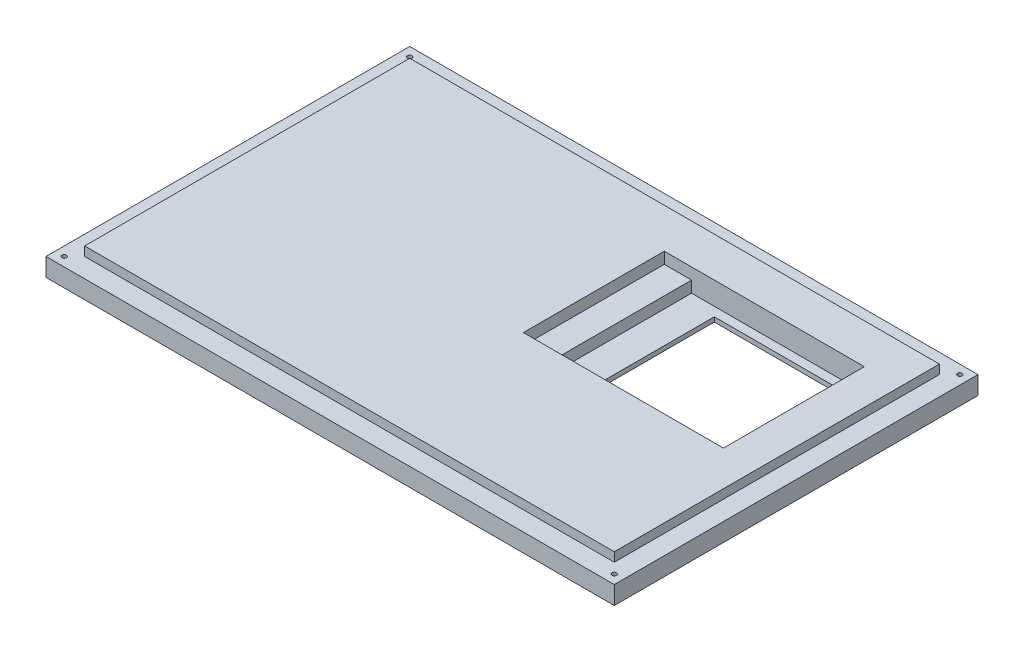
SolidWorks part; units mm, degrees
ref_plane "Front Plane" through (0, 0, 0) normal (0, 0, 1) x (1, 0, 0)
ref_plane "Top Plane" through (0, 0, 0) normal (0, 1, 0) x (1, 0, 0)
ref_plane "Right Plane" through (0, 0, 0) normal (1, 0, 0) x (0, 0, -1)
sketch "base sketch" plane through (0, 0, 0) normal (0, 1, 0) x (1, 0, 0)
  line L1 (0, 0) -> (125, 0)
  line L2 (0, 0) -> (0, 80)
  line L3 (0, 80) -> (125, 80)
  line L4 (125, 0) -> (125, 80)
  dimension "D1" = 80
  dimension "D2" = 125
extrude "base extrude" add sketch "base sketch" along normal blind 4
ref_plane "inset plane" through (0, 4, 0) normal (0, 1, 0) x (1, 0, 0)
sketch "inset sketch" plane through (0, 4, 0) normal (0, 1, 0) x (1, 0, 0)
  line L0 (0, 80) -> (0, 0) construction
  line L1 (4.25, 75.75) -> (120.75, 75.75)
  line L2 (4.25, 75.75) -> (4.25, 4.25)
  line L3 (4.25, 4.25) -> (120.75, 4.25)
  line L4 (120.75, 75.75) -> (120.75, 4.25)
  line L5 (125, 80) -> (0, 80) construction
  line L6 (125, 0) -> (125, 80) construction
  line L7 (0, 0) -> (125, 0) construction
  dimension "D1" = 4.25
  dimension "D2" = 4.25
  dimension "D3" = 4.25
  dimension "D4" = 4.25
extrude "inset extrude" add sketch "inset sketch" along normal blind 2
ref_plane "inner hole plane" through (0, 6, 0) normal (0, 1, 0) x (1, 0, 0)
sketch "inner hole sketch" plane through (0, 6, 0) normal (0, 1, 0) x (1, 0, 0)
  line L0 (125, 80) -> (0, 80) construction
  line L1 (82, 65) -> (110, 65)
  line L2 (82, 65) -> (82, 38)
  line L3 (82, 38) -> (110, 38)
  line L4 (110, 65) -> (110, 38)
  line L5 (125, 0) -> (125, 80) construction
  dimension "D1" = 28
  dimension "D2" = 27
  dimension "D3" = 15
  dimension "D4" = 15
extrude "inner hole cut" cut sketch "inner hole sketch" against normal blind 12
sketch "outer hole sketch" plane through (0, 6, 0) normal (0, 1, 0) x (1, 0, 0)
  line L0 (82, 65) -> (82, 38) construction
  line L1 (69, 67) -> (113, 67)
  line L2 (69, 67) -> (69, 36)
  line L3 (69, 36) -> (113, 36)
  line L4 (113, 67) -> (113, 36)
  line L5 (110, 65) -> (82, 65) construction
  dimension "D1" = 44
  dimension "D2" = 13
  dimension "D3" = 31
  dimension "D4" = 2
extrude "outter hole cut" cut sketch "outer hole sketch" against normal blind 2.5
sketch "middle hole sketch" plane through (0, 6, 0) normal (0, 1, 0) x (1, 0, 0)
  line L0 (113, 36) -> (113, 67) construction
  line L1 (113, 67) -> (75, 67)
  line L2 (113, 67) -> (113, 36)
  line L3 (113, 36) -> (75, 36)
  line L4 (75, 67) -> (75, 36)
  line L5 (113, 36) -> (113, 67) construction
  line L6 (69, 36) -> (113, 36) construction
  line L7 (69, 67) -> (69, 36) construction
  dimension "D1" = 6
  dimension "D2" = 31
extrude "middle hole cut" cut sketch "middle hole sketch" against normal blind 5
hole_wizard "Ø1.0mm Dowel Hole1" positions "3DSketch2" profile "Sketch7" hole size "Ø1.0" standard "ANSI Metric" end condition up to next
sketch3d "3DSketch2"
  line L0 (125, 0, 0) -> (125, 0, -80) construction
  line L1 (125, 0, -80) -> (0, 0, -80) construction
  line L2 (0, 0, 0) -> (125, 0, 0) construction
  line L3 (0, 0, -80) -> (0, 0, 0) construction
  point P0 (123, 0, -78)
  point P2 (123, 0, -2)
  point P4 (2, 0, -2)
  point P6 (2, 0, -78)
  point P17 (0, 0, 0)
  dimension "D1" = 2
  dimension "D2" = 2
  dimension "D3" = 2
  dimension "D4" = 2
  dimension "D5" = 2
  dimension "D6" = 2
  dimension "D7" = 2
  dimension "D8" = 2
sketch "Sketch7" plane through (123, 0, -78) normal (1, 0, 0) x (0, 0, -1)
  line L0 (0, 0) -> (0, 4)
  line L1 (0, 4) -> (0.5, 4)
  line L2 (0.5, 4) -> (0.5, 0)
  line L5 (0.5, 0) -> (0, 0)
  line L11 (0, -6.35) -> (0, 107.95) construction
  dimension "Thru Hole Dia." = 1
  dimension "Thru Hole Depth" = 4
